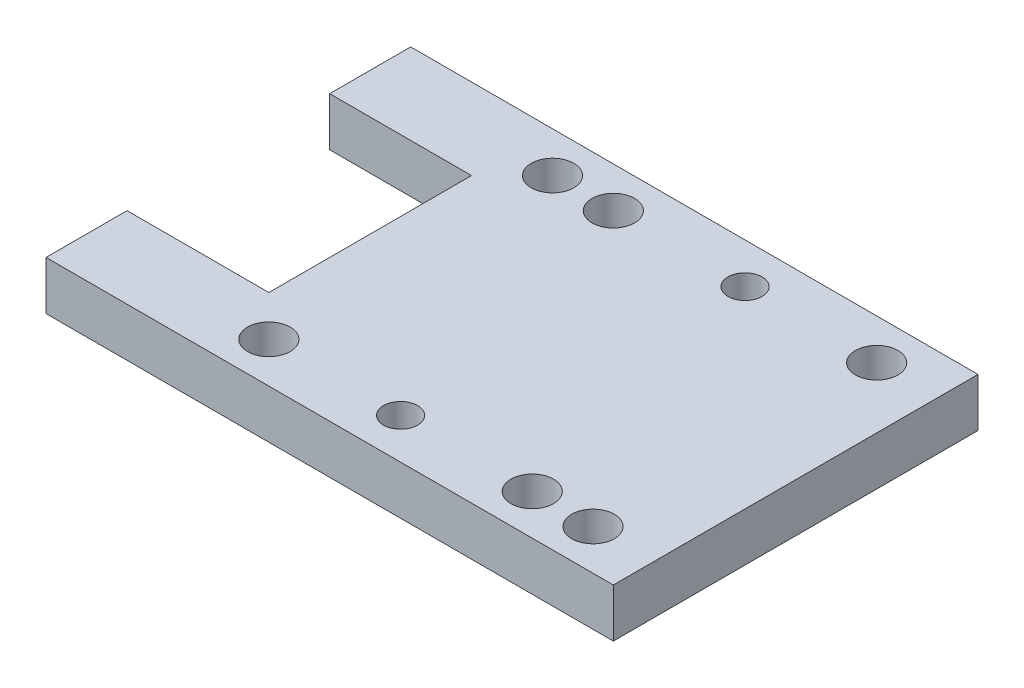
SolidWorks part; units mm, degrees
material "K110"
ref_plane "Front Plane" through (0, 0, 0) normal (0, 0, 1) x (1, 0, 0)
ref_plane "Top Plane" through (0, 0, 0) normal (0, 1, 0) x (1, 0, 0)
ref_plane "Right Plane" through (0, 0, 0) normal (1, 0, 0) x (0, 0, -1)
sketch "Sketch1" plane through (0, 0, 0) normal (0, 1, 0) x (1, 0, 0)
  line L1 (-70, -45) -> (70, -45)
  line L2 (-70, -45) -> (-70, 45)
  line L3 (-70, 45) -> (70, 45)
  line L4 (70, -45) -> (70, 45)
  line L5 (-70, -45) -> (70, 45) construction
  line L6 (-70, 45) -> (70, -45) construction
  point P0 (0, 0)
  dimension "D1" = 90
  dimension "D2" = 140
extrude "Boss-Extrude1" add sketch "Sketch1" against normal blind 12
sketch "Sketch2" plane through (0, 0, 0) normal (0, 1, 0) x (1, 0, 0)
  line L0 (-70, 45) -> (-70, -45) construction
  line L1 (-70, -25) -> (-35, -25)
  line L2 (-70, -25) -> (-70, 25)
  line L3 (-70, 25) -> (-35, 25)
  line L4 (-35, -25) -> (-35, 25)
  point P6 (-35, 0)
  dimension "D1" = 50
  dimension "D2" = 35
extrude "Cut-Extrude1" cut sketch "Sketch2" against normal up to next
hole_wizard "M10 Clearance Hole1" positions "Sketch6" profile "Sketch4" hole size "M10" standard "ISO" end condition through all
sketch "Sketch6" plane through (0, 0, 0) normal (0, 1, 0) x (1, 0, 0)
  point P12 (-10, 35)
  point P15 (55, 35)
  point P18 (40, -35)
  point P21 (-25, -35)
sketch "Sketch4" plane through (-10, 0, -35) normal (1, 0, 0) x (0, 0, 1)
  line L0 (0, 0) -> (0, 12)
  line L1 (0, 12) -> (5.25, 12)
  line L2 (5.25, 12) -> (5.25, 0)
  line L5 (5.25, 0) -> (0, 0)
  line L11 (0, -6.35) -> (0, 107.95) construction
  dimension "Thru Hole Dia." = 10.5
  dimension "Thru Hole Depth" = 12
hole_wizard "Ø10.5 (10.5) Diameter Hole1" positions "Sketch16" profile "Sketch8" hole size "Ø10.5" standard "ISO" end condition through all
sketch "Sketch16" plane through (0, 0, 0) normal (0, 1, 0) x (1, 0, 0)
  point P0 (-25, 35)
  point P3 (55, -35)
sketch "Sketch8" plane through (-25, 0, -35) normal (1, 0, 0) x (0, 0, 1)
  line L0 (0, 0) -> (0, 12)
  line L1 (0, 12) -> (5.25, 12)
  line L2 (5.25, 12) -> (5.25, 0)
  line L5 (5.25, 0) -> (0, 0)
  line L11 (0, -6.35) -> (0, 107.95) construction
  dimension "Thru Hole Dia." = 10.5
  dimension "Thru Hole Depth" = 12
hole_wizard "M8 Tapped Hole1" positions "Sketch12" profile "Sketch11" tap size "M8" standard "ISO"
sketch "Sketch12" plane through (-70, 0, 0) normal (-1, 0, 0) x (0, 0, 1)
  line L0 (45, -12) -> (45, 0) construction
  line L1 (-45, 0) -> (-25, 0) construction
  line L2 (25, 0) -> (45, 0) construction
  point P0 (35, -6)
  point P2 (-35, -6)
  point P7 (45, -6)
  point P10 (-35, 0)
  point P13 (35, 0)
sketch "Sketch11" plane through (-70, -6, 35) normal (0, 1, 0) x (0, 0, 1)
  line L0 (0, 0) -> (0, 22.25)
  line L1 (0, 22.25) -> (3.4, 20.2071)
  line L2 (3.4, 20.2071) -> (3.4, 0)
  line L5 (3.4, 0) -> (0, 0)
  line L10 (0, 22.25) -> (-3.4, 20.2071) construction
  line L11 (0, -6.35) -> (0, 107.95) construction
  dimension "Tap Drill Dia." = 6.8
  dimension "Tap Drill Depth" = 22.25
  dimension "Drill Angle" = 118
cosmetic thread "Hole Thread1"
cosmetic thread "Hole Thread2"
hole_wizard "M8 Clearance Hole1" positions "Sketch15" profile "Sketch14" hole size "M8" standard "ISO" end condition through all
sketch "Sketch15" plane through (0, 0, 0) normal (0, 1, 0) x (1, 0, 0)
  point P0 (22.5, 35)
  point P3 (7.5, -35)
sketch "Sketch14" plane through (22.5, 0, -35) normal (1, 0, 0) x (0, 0, 1)
  line L0 (0, 0) -> (0, 12)
  line L1 (0, 12) -> (4.2, 12)
  line L2 (4.2, 12) -> (4.2, 0)
  line L5 (4.2, 0) -> (0, 0)
  line L11 (0, -6.35) -> (0, 107.95) construction
  dimension "Thru Hole Dia." = 8.4
  dimension "Thru Hole Depth" = 12
